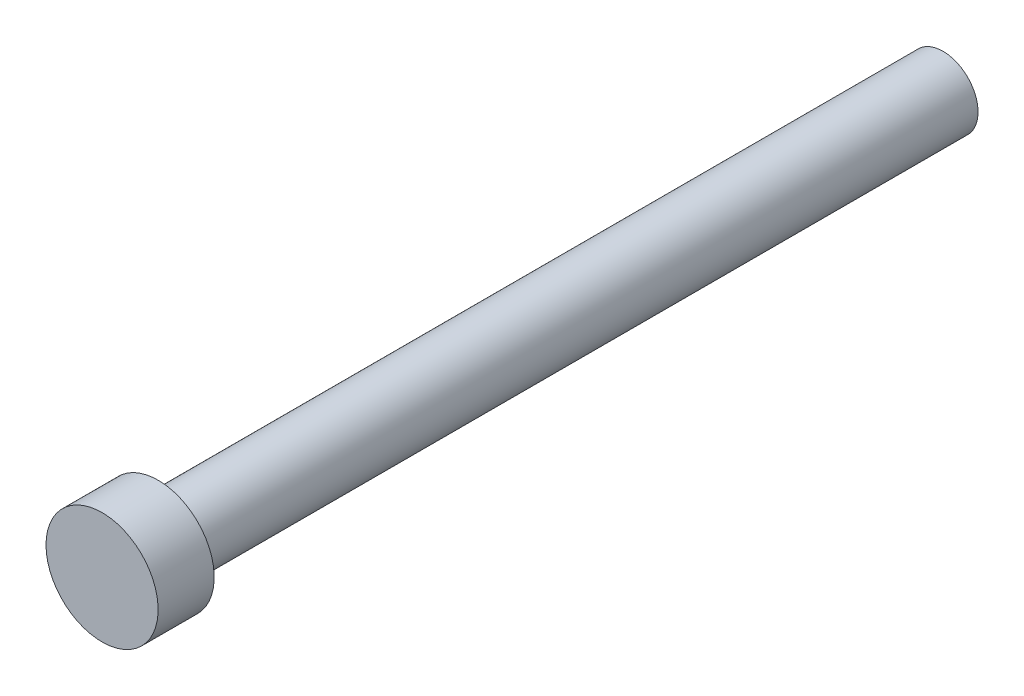
SolidWorks part; units mm, degrees
ref_plane "Front Plane" through (0, 0, 0) normal (0, 0, 1) x (1, 0, 0)
ref_plane "Top Plane" through (0, 0, 0) normal (0, 1, 0) x (1, 0, 0)
ref_plane "Right Plane" through (0, 0, 0) normal (1, 0, 0) x (0, 0, -1)
ref_plane "Plane1" through (0, 0, 0) normal (0, -1, 0) x (1, 0, 0)
sketch "Sketch1" plane through (0, 0, 0) normal (0, -1, 0) x (1, 0, 0)
  line L0 (5.08, 76.2) -> (0, 76.2)
  line L1 (0, 76.2) -> (0, 0)
  line L2 (0, 0) -> (3.175, 0)
  line L3 (3.175, 0) -> (3.175, 71.12)
  line L4 (3.175, 71.12) -> (5.08, 71.12)
  line L5 (5.08, 71.12) -> (5.08, 76.2)
  line L6 (0, 76.2) -> (0, 0) construction
  dimension "D1" = 3.175
  dimension "D2" = 5.08
  dimension "D3" = 76.2
  dimension "D4" = 5.08
revolve "Revolve1" add sketch "Sketch1" angle 360 about L6
